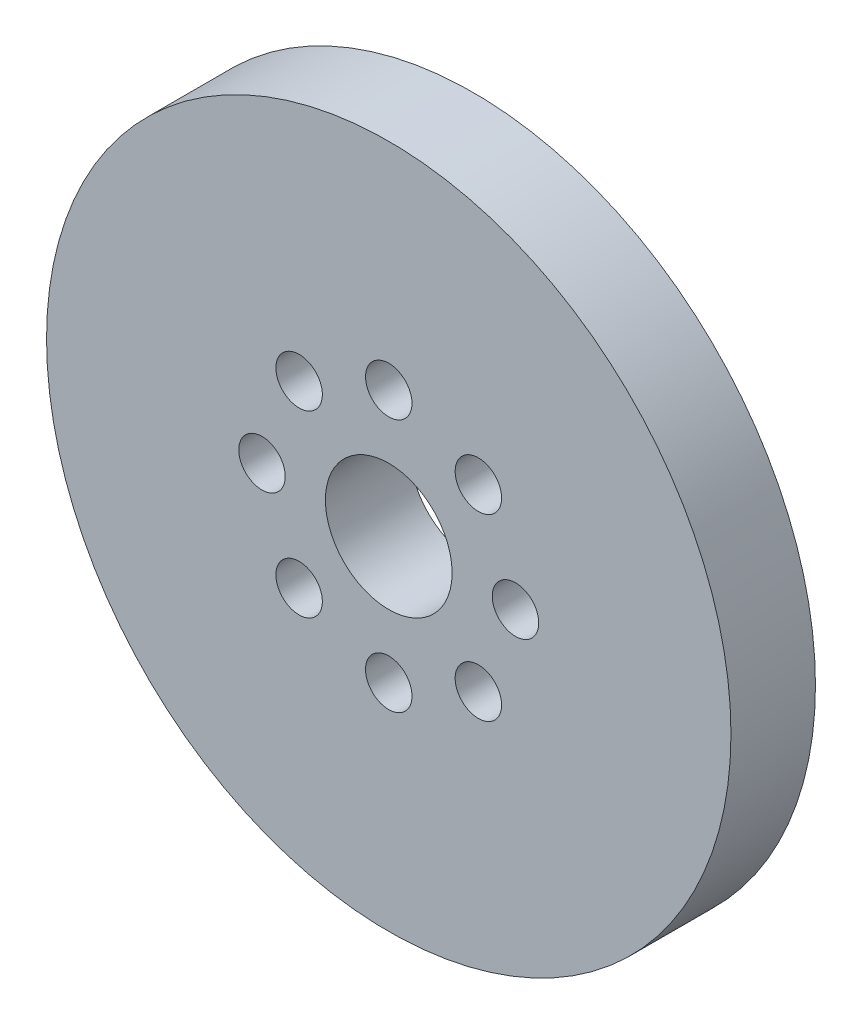
SolidWorks part; units mm, degrees
ref_plane "Front Plane" through (0, 0, 0) normal (0, 0, 1) x (1, 0, 0)
ref_plane "Top Plane" through (0, 0, 0) normal (0, 1, 0) x (1, 0, 0)
ref_plane "Right Plane" through (0, 0, 0) normal (1, 0, 0) x (0, 0, -1)
sketch "Sketch1" plane through (0, 0, 0) normal (0, 0, 1) x (1, 0, 0)
  circle A0 centre (0, 0) radius 40.5
  circle A1 centre (0, 0) radius 7.5
  dimension "D1" = 81
  dimension "D2" = 15
extrude "1/4" add sketch "Sketch1" along normal blind 10
sketch "Sketch2" plane through (0, 0, 0) normal (0, 0, 1) x (1, 0, 0)
  circle A0 centre (0, 0) radius 15 construction
  circle A1 centre (0, 15) radius 2.75
  point P17 (0, 0)
  dimension "D1" = 30
  dimension "D2" = 5.5
extrude "M5_through" cut sketch "Sketch2" along normal up to surface (10 mm away) up to face at (40.5, 0, 10)
pattern_circular "CirPattern5" count 8 over 360 about axis through (0, 0, 0) along (0, 0, 1) of "M5_through"
